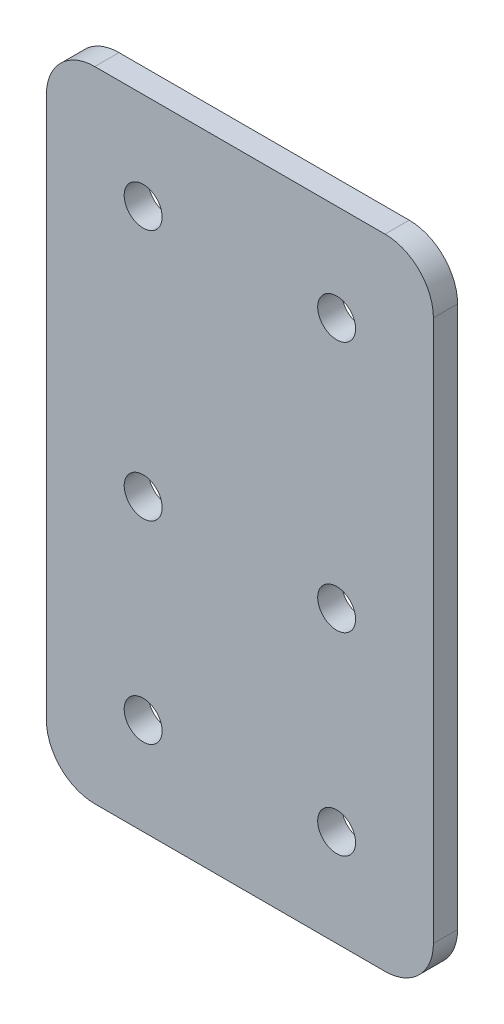
SolidWorks part; units mm, degrees
material "6061-T6 (SS)"
ref_plane "Front Plane" through (0, 0, 0) normal (0, 0, 1) x (1, 0, 0)
ref_plane "Top Plane" through (0, 0, 0) normal (0, 1, 0) x (1, 0, 0)
ref_plane "Right Plane" through (0, 0, 0) normal (1, 0, 0) x (0, 0, -1)
sketch "Sketch2" plane through (0, 0, 0) normal (0, 0, 1) x (1, 0, 0)
  line L1 (0, 0) -> (50.8, 0)
  line L2 (0, 0) -> (0, 83.82)
  line L3 (0, 83.82) -> (50.8, 83.82)
  line L6 (50.8, 83.82) -> (50.8, 0)
  dimension "D1" = 50.8
  dimension "D2" = 83.82
extrude "Boss-Extrude1" add sketch "Sketch2" against normal blind 3.175
sketch "Sketch3" plane through (0, 0, 0) normal (0, 0, 1) x (1, 0, 0)
  line L0 (50.8, 83.82) -> (0, 83.82) construction
  line L1 (0, 83.82) -> (0, 0) construction
  circle A0 centre (12.7, 71.12) radius 2.4892
  circle A17 centre (38.1, 71.12) radius 2.4892
  circle A24 centre (12.7, 38.1) radius 2.4892
  circle A25 centre (12.7, 12.7) radius 2.4892
  circle A26 centre (12.7, -12.7) radius 2.4892
  circle A27 centre (12.7, -38.1) radius 2.4892
  circle A28 centre (12.7, -63.5) radius 2.4892
  circle A33 centre (38.1, 12.7) radius 2.4892
  circle A34 centre (38.1, -12.7) radius 2.4892
  circle A35 centre (38.1, -38.1) radius 2.4892
  circle A36 centre (38.1, -63.5) radius 2.4892
  circle A41 centre (38.1, 38.1) radius 2.4892
  dimension "D1" = 4.9784
  dimension "D6" = 4.9784
  dimension "D5" = 4.9784
  dimension "D2" = 12.7
  dimension "D3" = 12.7
  dimension "D7" = 12.7
  dimension "D8" = 33.02
  dimension "D4" = 1
  dimension "D9" = 5
  dimension "D10" = 2
extrude "Cut-Extrude1" cut sketch "Sketch3" against normal through all
fillet "Fillet1" radius 6.35 4 edges at (0, 0, -1.5875) (0, 83.82, -1.5875) (50.8, 0, -1.5875) (50.8, 83.82, -1.5875)
